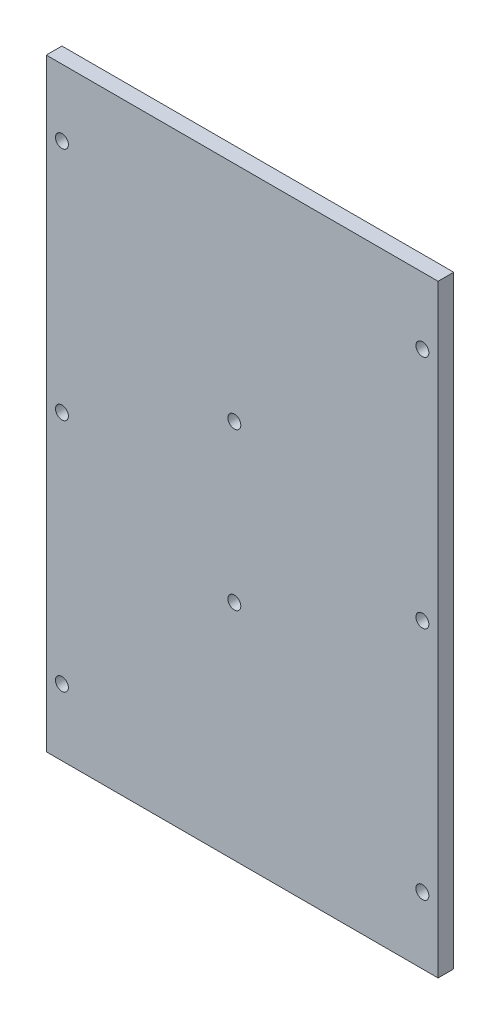
SolidWorks part; units mm, degrees
ref_plane "Front Plane" through (0, 0, 0) normal (1, 0, 0) x (0, 1, 0)
ref_plane "Top Plane" through (0, 0, 0) normal (0, 0, 1) x (0, 1, 0)
ref_plane "Right Plane" through (0, 0, 0) normal (0, 1, 0) x (-1, 0, 0)
sketch "Sketch1" plane through (0, 0, 0) normal (0, 0, 1) x (0, 1, 0)
  line L1 (0, 0) -> (154, 0)
  line L2 (0, 0) -> (0, 100)
  line L3 (0, 100) -> (154, 100)
  line L4 (154, 0) -> (154, 100)
  dimension "D1" = 154
  dimension "D2" = 100
extrude "Boss-Extrude1" add sketch "Sketch1" along normal blind 4
sketch "Sketch2" plane through (0, 0, 0) normal (0, 0, -1) x (1, 0, 0)
  line L0 (-4, 0) -> (-4, -154) construction
  line L1 (-100, 0) -> (0, 0) construction
  line L2 (0, -154) -> (-100, -154) construction
  line L3 (0, 0) -> (0, -154) construction
  line L4 (-4, -137) -> (-100, -137) construction
  line L5 (-100, -154) -> (-100, 0) construction
  line L6 (-4, -77) -> (-100, -77) construction
  line L7 (-4, -17) -> (-100, -17) construction
  line L8 (-96, 0) -> (-96, -154) construction
  line L9 (-52, -57) -> (-52, -97) construction
  circle A0 centre (-4, -77) radius 1.65
  circle A1 centre (-4, -17) radius 1.65
  circle A2 centre (-4, -137) radius 1.65
  circle A3 centre (-96, -137) radius 1.65
  circle A4 centre (-96, -77) radius 1.65
  circle A5 centre (-96, -17) radius 1.65
  circle A7 centre (-52, -97) radius 1.65
  circle A8 centre (-52, -57) radius 1.65
  point P14 (-4, -77)
  point P28 (-52, -77)
  point P34 (0, 0)
  dimension "D2" = 3.3
  dimension "D1" = 4
  dimension "D3" = 60
  dimension "D4" = 60
  dimension "D5" = 4
  dimension "D6" = 20
  dimension "D7" = 20
extrude "Cut-Extrude1" cut sketch "Sketch2" against normal through all
sketch "Sketch3" plane through (0, 0, 0) normal (0, 0, -1) x (1, 0, 0)
  line L0 (-85, 0) -> (-85, -153.2007) construction
  line L1 (-100, 0) -> (0, 0) construction
  line L2 (-15, 0) -> (-15, -154) construction
  line L3 (0, -154) -> (-100, -154) construction
  line L4 (-100, -139) -> (0, -139) construction
  line L5 (-100, -154) -> (-100, 0) construction
  line L6 (0, 0) -> (0, -154) construction
  line L7 (-100, -15) -> (0, -15) construction
  circle A0 centre (-85, -15) radius 7.5
  circle A1 centre (-15, -15) radius 7.5
  circle A2 centre (-15, -139) radius 7.5
  circle A3 centre (-85, -139) radius 7.5
  dimension "D5" = 15
  dimension "D1" = 15
  dimension "D2" = 15
  dimension "D3" = 15
  dimension "D4" = 15
extrude "Boss-Extrude2" add sketch "Sketch3" along normal blind 6 draft 15
sketch "Sketch4" plane through (0, 0, 0) normal (0, 0, -1) x (1, 0, 0)
  circle A0 centre (-96, -17) radius 3
  circle A1 centre (-4, -17) radius 3
  circle A2 centre (-4, -77) radius 3
  circle A3 centre (-96, -77) radius 3
  circle A4 centre (-96, -137) radius 3
  circle A5 centre (-4, -137) radius 3
  circle A6 centre (-52, -57) radius 3
  circle A8 centre (-52, -97) radius 3
  dimension "D1" = 6
extrude "Cut-Extrude2" cut sketch "Sketch4" against normal blind 1.5
